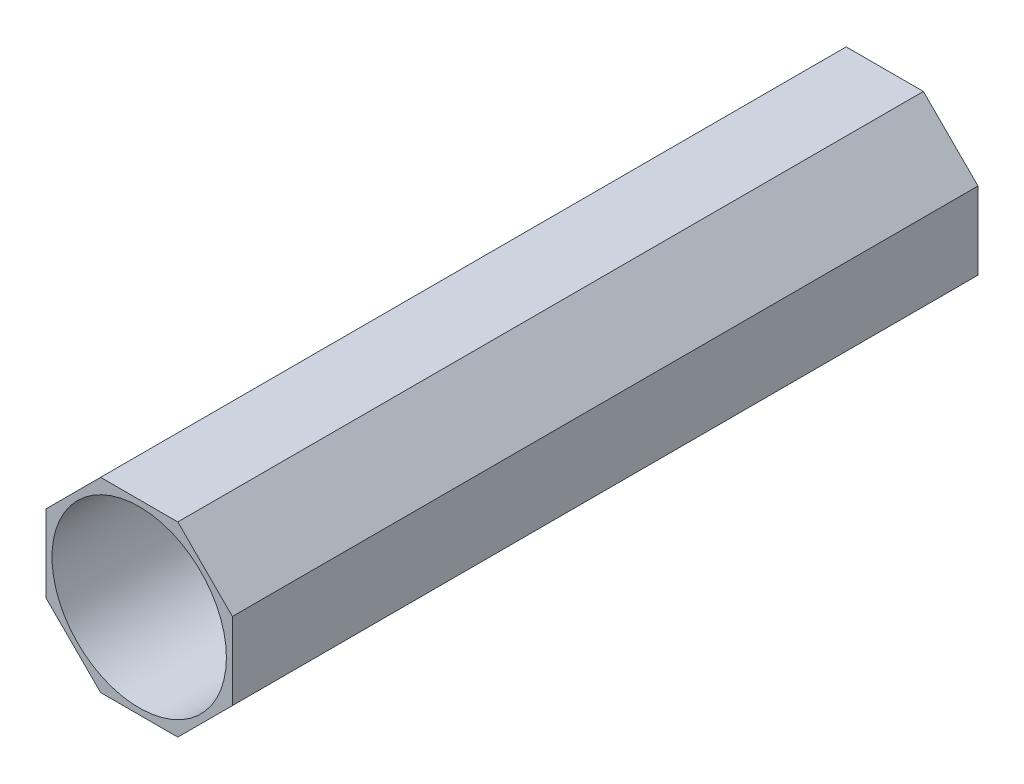
SolidWorks part; units mm, degrees
ref_plane "정면" through (0, 0, 0) normal (0, 0, 1) x (1, 0, 0)
ref_plane "윗면" through (0, 0, 0) normal (0, 1, 0) x (1, 0, 0)
ref_plane "우측면" through (0, 0, 0) normal (1, 0, 0) x (0, 0, -1)
sketch "스케치1" plane through (0, 0, 0) normal (0, 0, 1) x (1, 0, 0)
  circle A0 centre (0, 0) radius 14.05
  circle A1 centre (0, 0) radius 15.95
  dimension "D1" = 28.1
  dimension "D2" = 31.9
extrude "보스-돌출1" add sketch "스케치1" against normal blind 2
sketch "스케치2" plane through (0, 0, 0) normal (0, 0, 1) x (1, 0, 0)
  circle A0 centre (0, 0) radius 22.5
  circle A1 centre (0, 0) radius 11
  dimension "D1" = 45
  dimension "D2" = 22
extrude "보스-돌출2" add sketch "스케치2" along normal blind 50
sketch "스케치3" plane through (0, 0, 0) normal (0, 0, 1) x (1, 0, 0)
  line L1 (-9.3198, -22.5) -> (9.3198, -22.5)
  line L2 (9.3198, -22.5) -> (22.5, -9.3198)
  line L3 (22.5, -9.3198) -> (22.5, 9.3198)
  line L4 (22.5, 9.3198) -> (9.3198, 22.5)
  line L5 (9.3198, 22.5) -> (-9.3198, 22.5)
  line L6 (-9.3198, 22.5) -> (-22.5, 9.3198)
  line L7 (-22.5, 9.3198) -> (-22.5, -9.3198)
  line L8 (-22.5, -9.3198) -> (-9.3198, -22.5)
  circle A0 centre (0, 0) radius 21.05
  circle A1 centre (0, 0) radius 22.5 construction
  dimension "D1" = 42.1
  dimension "D2" = 45
extrude "보스-돌출3" add sketch "스케치3" against normal mid plane 140
sketch "스케치5" plane through (0, 0, 70) normal (0, 0, 1) x (1, 0, 0)
  line L8 (-22.5, -9.3198) -> (-9.3198, -22.5)
  line L9 (-9.3198, -22.5) -> (9.3198, -22.5)
  line L10 (9.3198, -22.5) -> (22.5, -9.3198)
  line L11 (22.5, -9.3198) -> (22.5, 9.3198)
  line L12 (22.5, 9.3198) -> (9.3198, 22.5)
  line L13 (9.3198, 22.5) -> (-9.3198, 22.5)
  line L14 (-9.3198, 22.5) -> (-22.5, 9.3198)
  line L15 (-22.5, 9.3198) -> (-22.5, -9.3198)
  line L16 (-22.5, -9.3198) -> (-9.3198, -22.5)
  line L17 (-9.3198, -22.5) -> (9.3198, -22.5)
  line L18 (9.3198, -22.5) -> (22.5, -9.3198)
  line L19 (22.5, -9.3198) -> (22.5, 9.3198)
  line L20 (22.5, 9.3198) -> (9.3198, 22.5)
  line L21 (9.3198, 22.5) -> (-9.3198, 22.5)
  line L22 (-9.3198, 22.5) -> (-22.5, 9.3198)
  line L23 (-22.5, 9.3198) -> (-22.5, -9.3198)
  circle A0 centre (0, 0) radius 21.05
  dimension "D1" = 0
extrude "보스-돌출5" add sketch "스케치5" along normal blind 40
